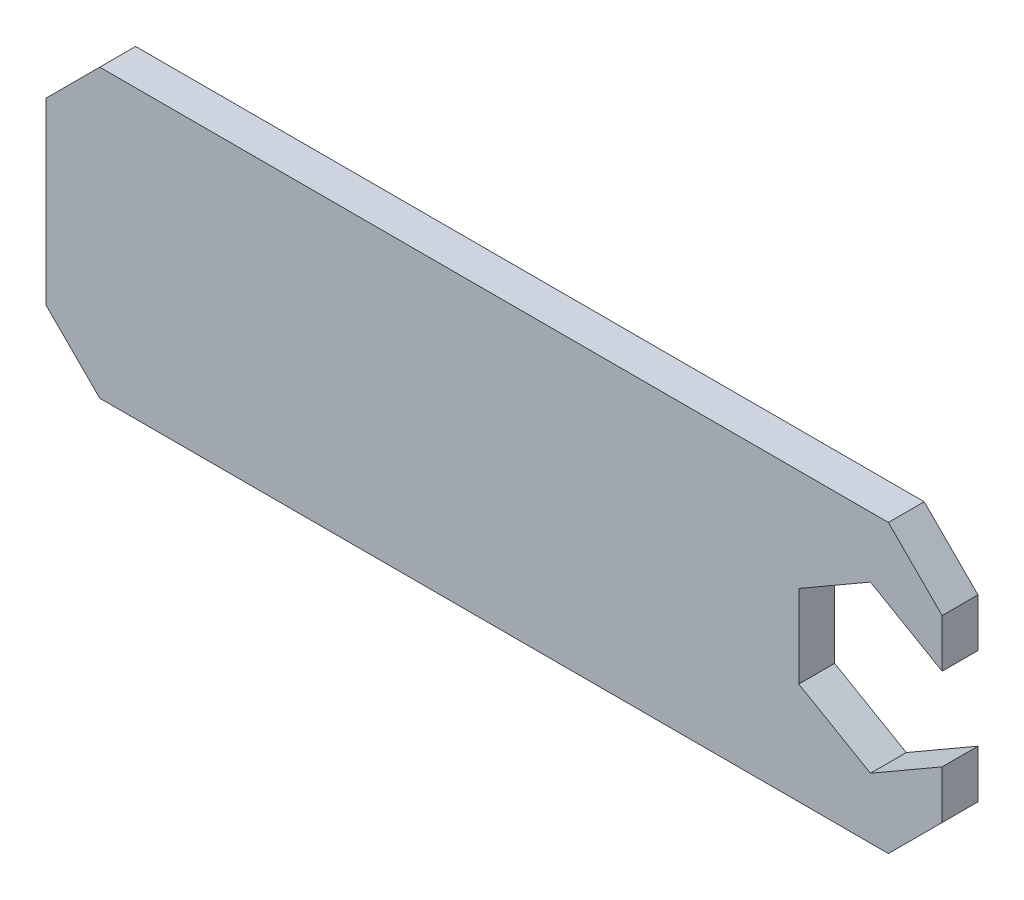
SolidWorks part; units mm, degrees
ref_plane "정면" through (0, 0, 0) normal (0, 0, 1) x (1, 0, 0)
ref_plane "윗면" through (0, 0, 0) normal (0, 1, 0) x (1, 0, 0)
ref_plane "우측면" through (0, 0, 0) normal (1, 0, 0) x (0, 0, -1)
sketch "스케치1" plane through (0, 0, 0) normal (0, 0, 1) x (1, 0, 0)
  line L0 (0, 13) -> (3, 16)
  line L1 (0, 0) -> (50, 0)
  line L2 (0, 0) -> (0, 16)
  line L3 (0, 16) -> (50, 16)
  line L4 (50, 0) -> (50, 16)
  line L5 (0, 3) -> (3, 0)
  line L6 (47, 0) -> (50, 3)
  line L7 (50, 13) -> (47, 16)
  dimension "D1" = 16
  dimension "D2" = 50
  dimension "D3" = 3
  dimension "D4" = 3
  dimension "D5" = 3
  dimension "D6" = 3
  dimension "D7" = 3
  dimension "D8" = 3
  dimension "D9" = 3
  dimension "D10" = 3
extrude "보스-돌출1" add sketch "스케치1" along normal blind 2 contours L4 L7 L3 L0 L2 L5 L1 L6
sketch "스케치2" plane through (0, 0, 2) normal (0, 0, 1) x (1, 0, 0)
  line L13 (3, 0) -> (47, 0) construction
  line L14 (46, 12.6188) -> (42, 10.3094)
  line L15 (42, 10.3094) -> (42, 5.6906)
  line L16 (42, 5.6906) -> (46, 3.3812)
  line L17 (46, 3.3812) -> (50, 5.6906)
  line L18 (50, 5.6906) -> (50, 10.3094)
  line L19 (50, 10.3094) -> (46, 12.6188)
  line L20 (50, 3) -> (50, 13) construction
  circle A0 centre (46, 8) radius 4 construction
  point P1 (0, 0)
  dimension "D3" = 8
  dimension "D2" = 8
extrude "컷-돌출1" cut sketch "스케치2" against normal blind 10
